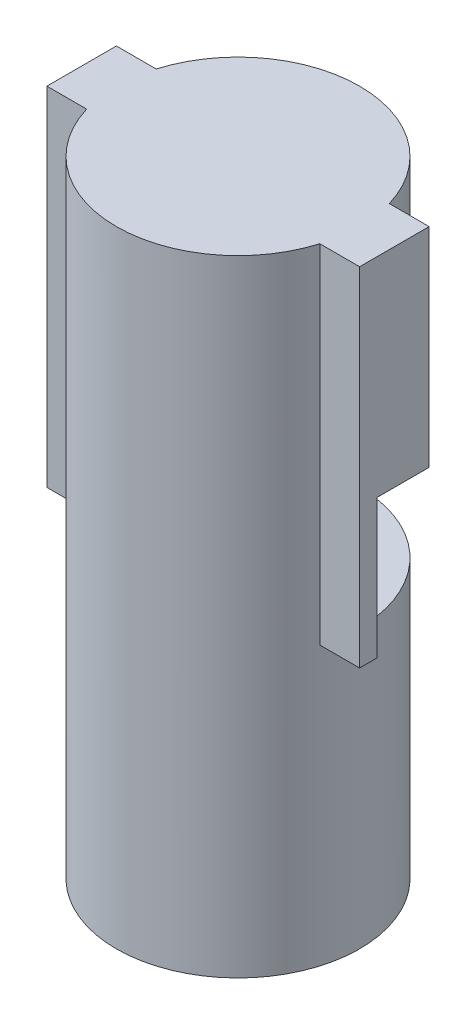
SolidWorks part; units mm, degrees
ref_plane "Спереди" through (0, 0, 0) normal (0, 0, 1) x (1, 0, 0)
ref_plane "Сверху" through (0, 0, 0) normal (0, 1, 0) x (1, 0, 0)
ref_plane "Справа" through (0, 0, 0) normal (1, 0, 0) x (0, 0, -1)
sketch "Sketch1" plane through (0, 0, 0) normal (0, 1, 0) x (1, 0, 0)
  circle A0 centre (0, 0) radius 3.5
  dimension "D1" = 7
extrude "Boss-Extrude1" add sketch "Sketch1" along normal blind 18
sketch "Sketch2" plane through (0, 18, 0) normal (0, 1, 0) x (1, 0, 0)
  line L1 (4.5, 1) -> (-4.5, 1)
  line L2 (4.5, 1) -> (4.5, -1)
  line L3 (4.5, -1) -> (-4.5, -1)
  line L4 (-4.5, 1) -> (-4.5, -1)
  line L5 (4.5, 1) -> (-4.5, -1) construction
  line L6 (4.5, -1) -> (-4.5, 1) construction
  point P0 (0, 0)
  dimension "D1" = 2
  dimension "D2" = 9
extrude "Boss-Extrude3" add sketch "Sketch2" against normal blind 10
sketch "Sketch3" plane through (0, 0, 0) normal (0, -1, 0) x (1, 0, 0)
  line L0 (3.4641, 0.5) -> (-3.4641, 0.5) construction
  line L1 (-3.5, 0) -> (3.5, 0) construction
  line L3 (-5, 0.5) -> (5, 0.5)
  line L4 (-5, 0.5) -> (-5, -3.5)
  line L5 (-5, -3.5) -> (5, -3.5)
  line L6 (5, 0.5) -> (5, -3.5)
  line L7 (-5, 0.5) -> (5, -3.5) construction
  line L8 (-5, -3.5) -> (5, 0.5) construction
  circle A0 centre (0, 0) radius 3.5 construction
  point P7 (0, -1.5)
  point P12 (0, 0.5)
  point P13 (0, 0.5)
  point P14 (3.1438, -1.5384)
  point P15 (4.5804, -2.5937)
  point P16 (0, -3.5)
  dimension "D1" = 1
  dimension "D2" = 10
extrude "Cut-Extrude3" cut sketch "Sketch3" against normal blind 4 from offset 8
